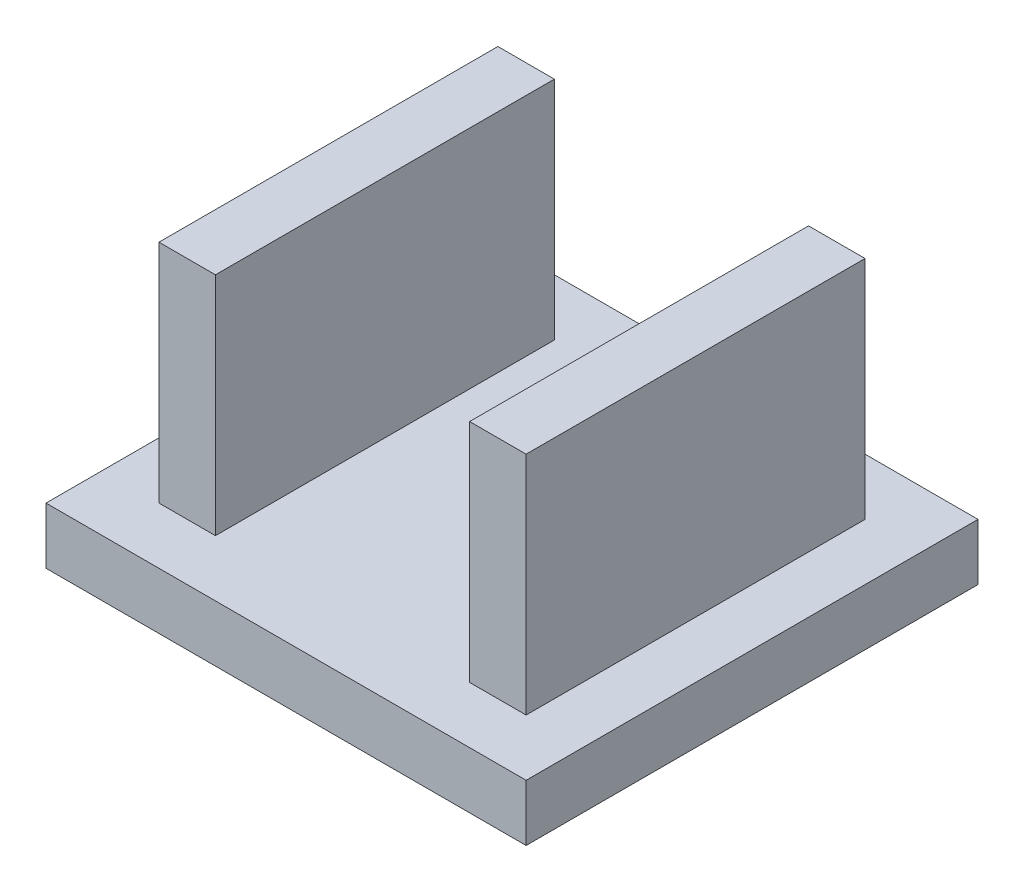
SolidWorks part; units mm, degrees
ref_plane "Plano frontal" through (0, 0, 0) normal (0, 0, 1) x (1, 0, 0)
ref_plane "Plano superior" through (0, 0, 0) normal (0, 1, 0) x (1, 0, 0)
ref_plane "Plano direito" through (0, 0, 0) normal (1, 0, 0) x (0, 0, -1)
sketch "Esboço1" plane through (0, 0, 0) normal (0, 1, 0) x (1, 0, 0)
  line L1 (-4.25, 4) -> (4.25, 4)
  line L2 (-4.25, 4) -> (-4.25, -4)
  line L3 (-4.25, -4) -> (4.25, -4)
  line L4 (4.25, 4) -> (4.25, -4)
  line L5 (-4.25, 4) -> (4.25, -4) construction
  line L6 (-4.25, -4) -> (4.25, 4) construction
  point P0 (0, 0)
  dimension "D1" = 8.5
  dimension "D2" = 8
extrude "Ressalto-extrusão1" add sketch "Esboço1" along normal blind 1
sketch "Esboço2" plane through (0, 1, 0) normal (0, 1, 0) x (1, 0, 0)
  line L1 (-3.25, 3) -> (-2.25, 3)
  line L2 (-3.25, 3) -> (-3.25, -3)
  line L3 (-3.25, -3) -> (-2.25, -3)
  line L4 (-2.25, 3) -> (-2.25, -3)
  line L5 (2.25, 3) -> (3.25, 3)
  line L6 (2.25, 3) -> (2.25, -3)
  line L7 (2.25, -3) -> (3.25, -3)
  line L8 (3.25, 3) -> (3.25, -3)
  dimension "D1" = 4.5
  dimension "D2" = 2.25
  dimension "D3" = 1
  dimension "D4" = 1
  dimension "D5" = 6
  dimension "D6" = 6
  dimension "D7" = 3
extrude "Ressalto-extrusão2" add sketch "Esboço2" along normal blind 4
